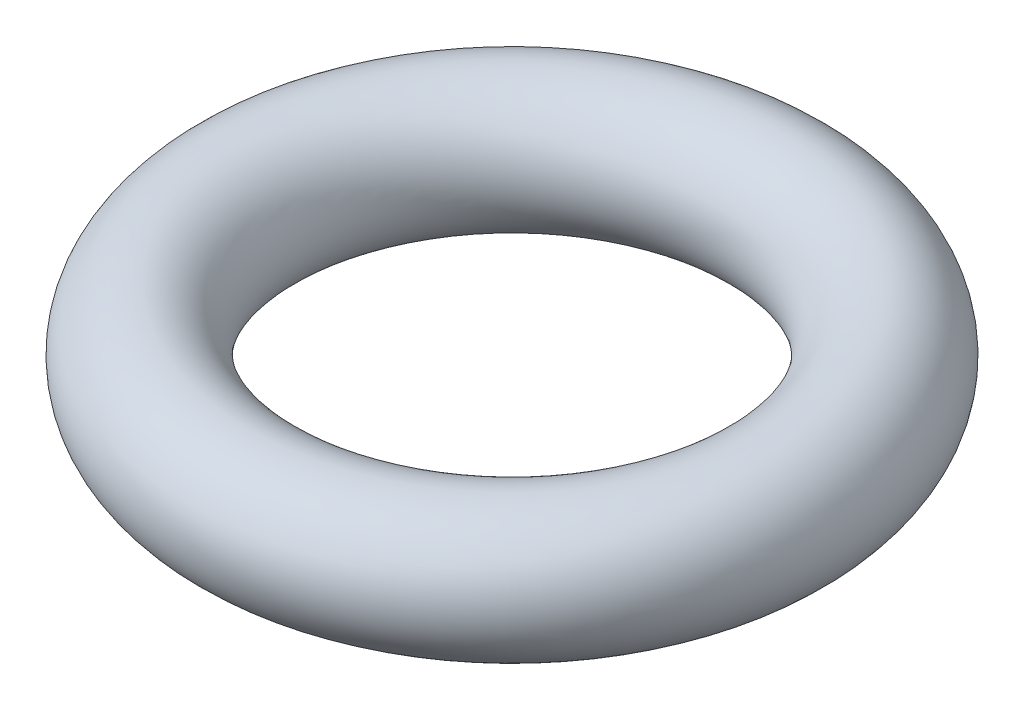
SolidWorks part; units mm, degrees
material "PTFE (general)"
ref_plane "Front Plane" through (0, 0, 0) normal (0, 0, 1) x (1, 0, 0)
ref_plane "Top Plane" through (0, 0, 0) normal (0, 1, 0) x (1, 0, 0)
ref_plane "Right Plane" through (0, 0, 0) normal (1, 0, 0) x (0, 0, -1)
sketch "Sketch1" plane through (0, 0, 0) normal (0, 0, 1) x (1, 0, 0)
  line L0 (0, 0) -> (0, 1.8558) construction
  line L1 (3.175, 0) -> (0, 0) construction
  circle A0 centre (3.175, 0) radius 0.7938
  dimension "D1" = 4.7625
  dimension "D2" = 1.5875
revolve "AS568-008" add sketch "Sketch1" angle 360 about L0
sketch "Sketch2" plane through (0, 0, 0) normal (0, 1, 0) x (1, 0, 0)
  circle A0 centre (0, 0) radius 2.3813
  dimension "D1" = 4.7625
